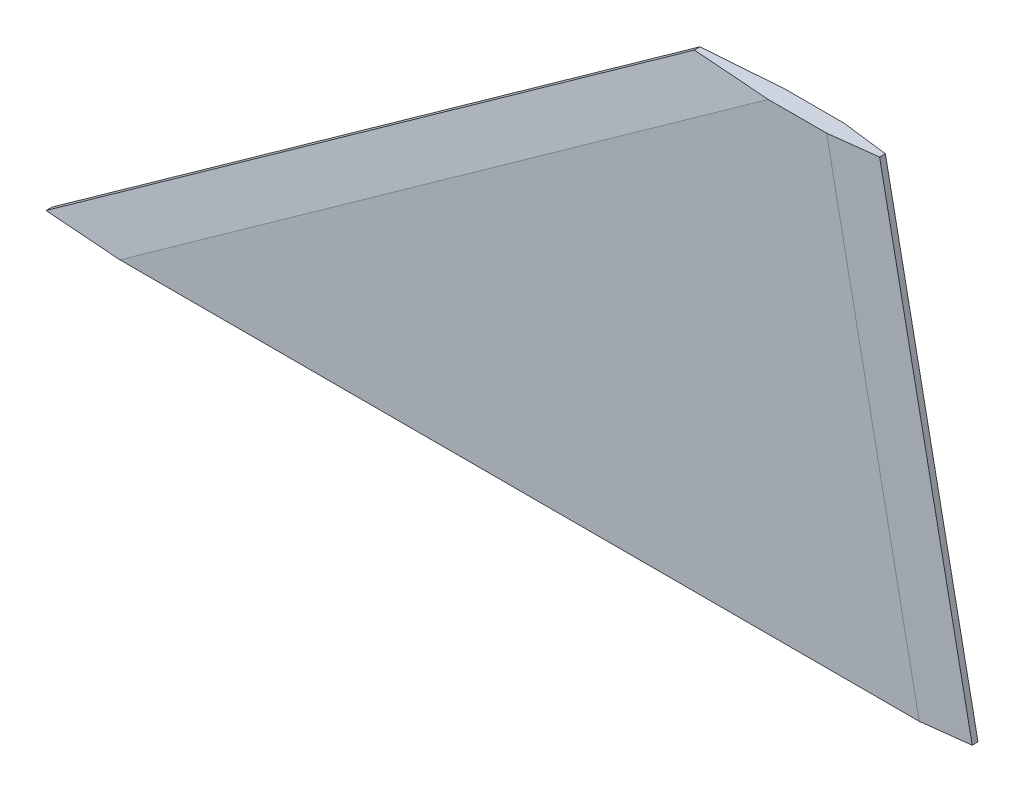
SolidWorks part; units mm, degrees
material "Hexcel AS4C (3000 Filaments)"
ref_plane "Front Plane" through (0, 0, 0) normal (0, 0, 1) x (1, 0, 0)
ref_plane "Top Plane" through (0, 0, 0) normal (0, 1, 0) x (1, 0, 0)
ref_plane "Right Plane" through (0, 0, 0) normal (1, 0, 0) x (0, 0, -1)
sketch "Sketch1" plane through (0, 0, 0) normal (0, 0, 1) x (1, 0, 0)
  line L0 (0, 0) -> (254, 0)
  line L1 (254, 0) -> (228.6, 127)
  line L2 (228.6, 127) -> (177.8, 127)
  line L3 (177.8, 127) -> (0, 0)
  dimension "D1" = 254
  dimension "D2" = 127
  dimension "D3" = 50.8
  dimension "D4" = 177.8
extrude "Boss-Extrude1" add sketch "Sketch1" along normal blind 4.7625
chamfer "Chamfer1" distance 1.5875 distance2 12.7 2 edges at (88.9, 63.5, 0) (88.9, 63.5, 4.7625)
chamfer "Chamfer2" distance 1.5875 distance2 12.7 2 edges at (241.3, 63.5, 0) (241.3, 63.5, 4.7625)
sketch "RASAero Fin Measurements" plane through (0, 0, 4.7625) normal (0, 0, 1) x (1, 0, 0)
  line L0 (88.9, 63.5) -> (110.7499, 63.5) construction
  line L1 (0, 0) -> (177.8, 127) construction
  line L2 (228.6, 127) -> (254, 0) construction
  line L3 (21.8499, 0) -> (241.0485, 0) construction
  line L4 (241.0485, 0) -> (215.6485, 127) construction
  line L5 (199.6499, 127) -> (21.8499, 0) construction
  line L6 (241.0485, 0) -> (215.6485, 127)
  line L7 (199.6499, 127) -> (21.8499, 0)
  line L8 (228.3485, 63.5) -> (241.3, 63.5) construction
  dimension "D1" = 63.5
